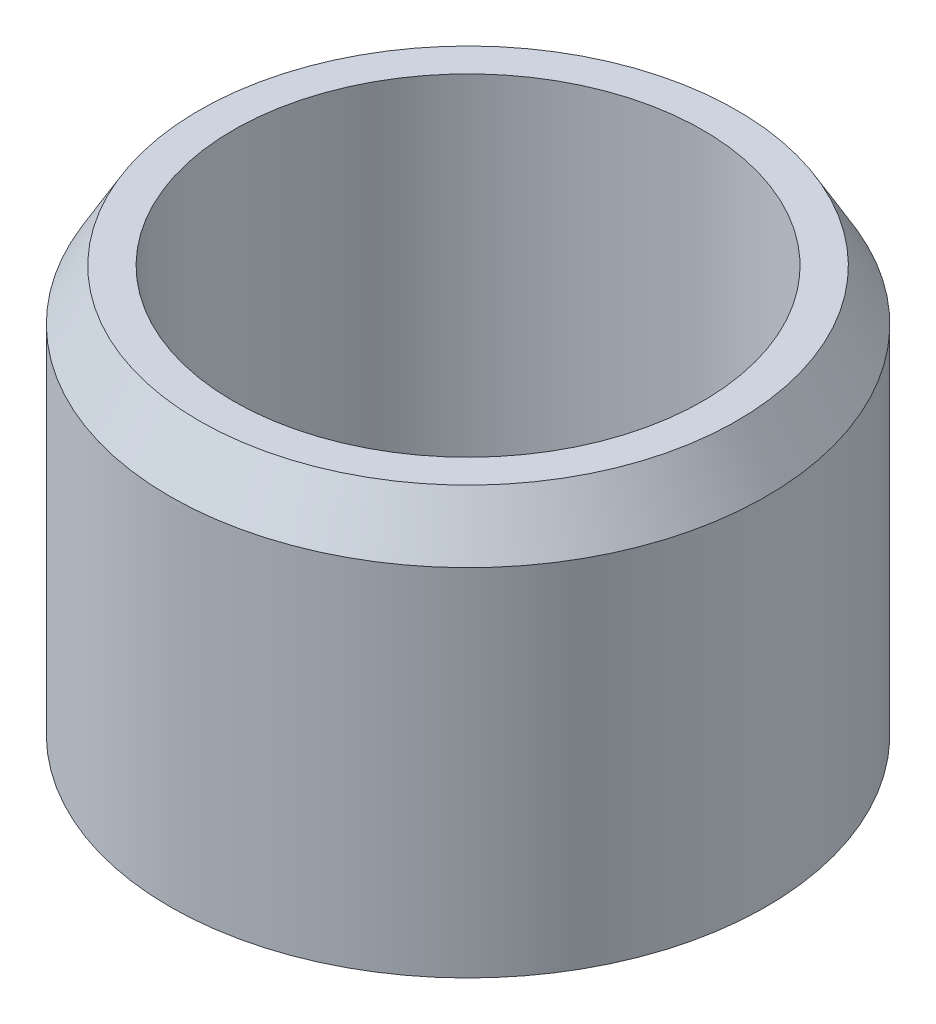
SolidWorks part; units mm, degrees
ref_plane "Front Plane" through (0, 0, 0) normal (0, 0, 1) x (1, 0, 0)
ref_plane "Top Plane" through (0, 0, 0) normal (0, 1, 0) x (1, 0, 0)
ref_plane "Right Plane" through (0, 0, 0) normal (1, 0, 0) x (0, 0, -1)
sketch "Sketch1" plane through (0, 0, 0) normal (0, 1, 0) x (1, 0, 0)
  circle A0 centre (0, 0) radius 23.5
  dimension "D1" = 47
extrude "Boss-Extrude1" add sketch "Sketch1" along normal blind 32
sketch "Sketch2" plane through (0, 32, 0) normal (0, 1, 0) x (1, 0, 0)
  circle A0 centre (0, 0) radius 18.5
  dimension "D1" = 37
extrude "Cut-Extrude1" cut sketch "Sketch2" against normal blind 32
chamfer "Chamfer1" distance 4 angle 30 1 edges at (0, 32, 23.5)
